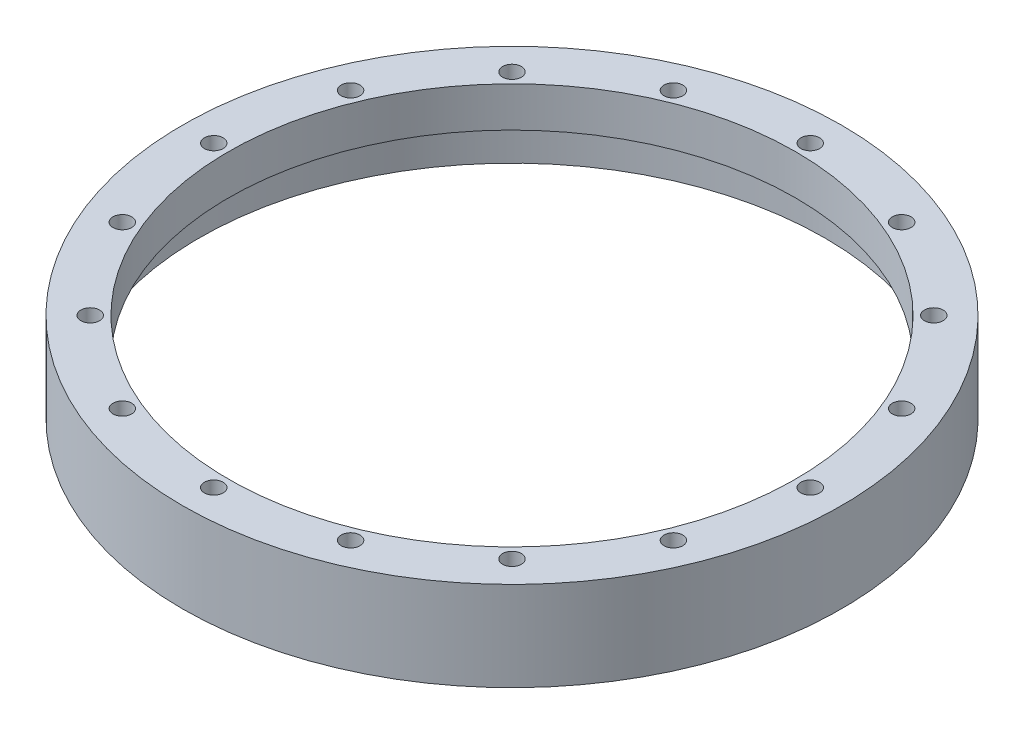
SolidWorks part; units mm, degrees
material "6061-T6 (SS)"
ref_plane "Front Plane" through (0, 0, 0) normal (0, 0, 1) x (1, 0, 0)
ref_plane "Top Plane" through (0, 0, 0) normal (0, 1, 0) x (1, 0, 0)
ref_plane "Right Plane" through (0, 0, 0) normal (1, 0, 0) x (0, 0, -1)
sketch "Sketch1" plane through (0, 0, 0) normal (0, 0, 1) x (1, 0, 0)
  line L0 (-49.4665, 0) -> (-57.4802, 0)
  line L1 (-57.4802, 0) -> (-57.4802, -15.5956)
  line L2 (-57.4802, -15.5956) -> (-54.5719, -15.5956)
  line L3 (-54.5719, -15.5956) -> (-54.5719, -6.985)
  line L4 (-54.5719, -6.985) -> (-49.4665, -6.985)
  line L5 (-49.4665, -6.985) -> (-49.4665, 0)
  line L6 (0, 0) -> (0, 8.0765) construction
  dimension "D1" = 49.4665
  dimension "D2" = 54.5719
  dimension "D3" = 57.4802
  dimension "D4" = 15.5956
  dimension "D5" = 6.985
revolve "Revolve1" add sketch "Sketch1" angle 360 about L6
sketch "Sketch2" plane through (0, 0, 0) normal (0, 1, 0) x (1, 0, 0)
  line L0 (0, 49.4665) -> (0, 52.0192) construction
  circle A0 centre (0, 0) radius 49.4665 construction
  dimension "D1" = 52.0192
hole_wizard "#4 Clearance Hole1" positions "3DSketch1" profile "Sketch3" hole size "#4" standard "Ansi Inch"
sketch3d "3DSketch1"
  point P0 (0, 0, -52.0192)
sketch "Sketch3" plane through (0, 0, -52.0192) normal (1, 0, 0) x (0, 0, 1)
  line L0 (0, 0) -> (0, 11.1406)
  line L1 (0, 11.1406) -> (1.6319, 10.16)
  line L2 (1.6319, 10.16) -> (1.6319, 0)
  line L5 (1.6319, 0) -> (0, 0)
  line L10 (0, 11.1406) -> (-1.632, 10.16) construction
  line L11 (0, -6.35) -> (0, 107.95) construction
  dimension "Hole Dia." = 3.2639
  dimension "Hole Depth" = 10.16
  dimension "Drill Angle" = 118
pattern_circular "CirPattern1" count 16 over 360 about axis through (0, 0, 0) along (0, 1, 0) of "#4 Clearance Hole1"
sketch "Sketch4" plane through (0, 0, 0) normal (0, 1, 0) x (1, 0, 0)
  line L0 (0, 0) -> (8.4341, 56.8581) construction
  line L1 (0, 0) -> (13.9665, 55.7576) construction
  line L3 (0, 0) -> (0, 49.4665) construction
  line L4 (8.4341, 56.8581) -> (7.2582, 48.9311)
  line L5 (13.9665, 55.7576) -> (12.0194, 47.9841)
  arc A0 (7.2582, 48.9311) -> (12.0194, 47.9841) centre (0, 0) cw
  circle A1 centre (0, 0) radius 49.4665 construction
  arc A2 (8.4341, 56.8581) -> (13.9665, 55.7576) centre (0, 0) cw
  circle A3 centre (0, 0) radius 57.4802 construction
  dimension "D1" = 5.625
  dimension "D2" = 8.438
